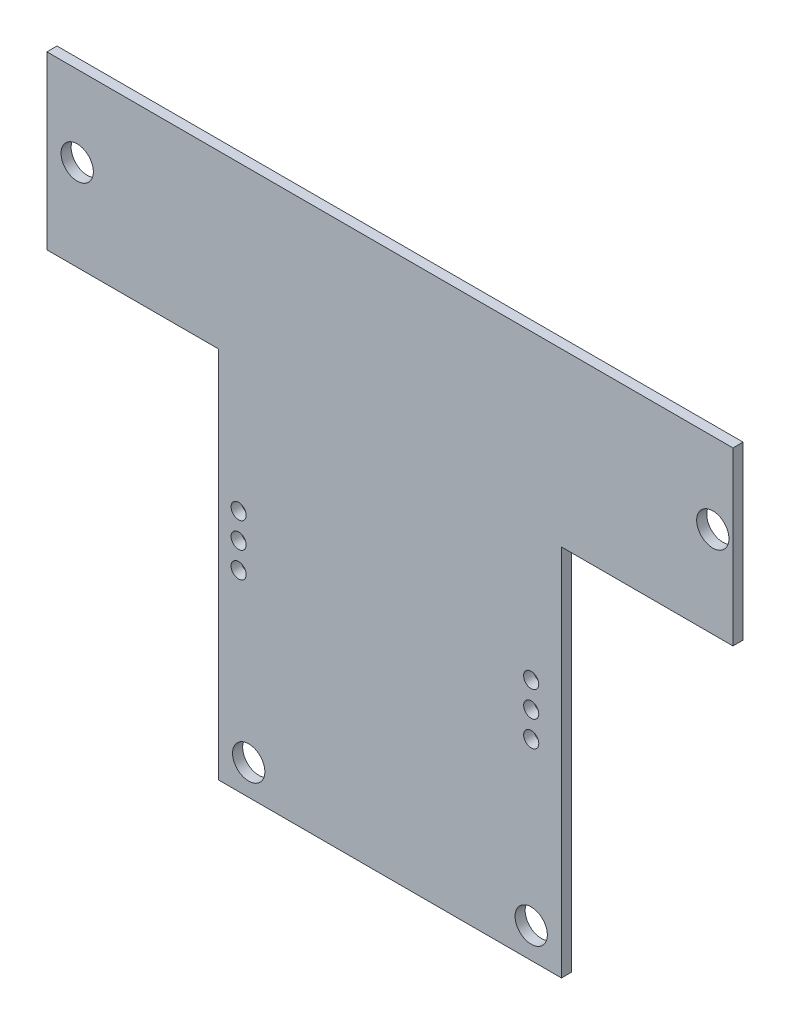
SolidWorks part; units mm, degrees
ref_plane "Ön Düzlem" through (0, 0, 0) normal (0, 0, 1) x (1, 0, 0)
ref_plane "Üst Düzlem" through (0, 0, 0) normal (0, 1, 0) x (1, 0, 0)
ref_plane "Sağ Düzlem" through (0, 0, 0) normal (1, 0, 0) x (0, 0, -1)
sketch "Çizim1" plane through (0, 0, 0) normal (0, 0, 1) x (1, 0, 0)
  line L0 (0, 0) -> (68, 0)
  line L1 (68, 0) -> (68, -17)
  line L2 (68, -17) -> (51, -17)
  line L3 (51, -17) -> (51, -54)
  line L4 (51, -54) -> (17, -54)
  line L5 (17, -54) -> (17, -17)
  line L6 (17, -17) -> (0, -17)
  line L7 (0, -17) -> (0, 0)
  line L8 (34, 0) -> (34, -54) construction
  line L9 (3, -8) -> (66, -8) construction
  line L10 (20, -51) -> (48, -51) construction
  circle A0 centre (3, -8) radius 1.6
  circle A1 centre (66, -8) radius 1.6
  circle A2 centre (20, -51) radius 1.6
  circle A3 centre (48, -51) radius 1.6
  dimension "D5" = 3.2
  dimension "D6" = 8
  dimension "D7" = 3
  dimension "D9" = 3.2
  dimension "D11" = 3.2
  dimension "D12" = 3
  dimension "D13" = 3
  dimension "D1" = 68
  dimension "D2" = 17
  dimension "D3" = 34
  dimension "D4" = 37
  dimension "D8" = 63
  dimension "D10" = 28
extrude "Yükseklik-Ekstrüzyon1" add sketch "Çizim1" along normal blind 1
sketch "Çizim2" plane through (0, 0, 1) normal (0, 0, 1) x (1, 0, 0)
  line L0 (19, -29.92) -> (19, -35) construction
  line L1 (17, -17) -> (17, -54) construction
  line L2 (48, -35) -> (48, -29.92) construction
  line L3 (17, -54) -> (51, -54) construction
  circle A0 centre (19, -35) radius 0.75
  circle A1 centre (19, -32.46) radius 0.75
  circle A2 centre (19, -29.92) radius 0.75
  circle A3 centre (48, -29.92) radius 0.75
  circle A4 centre (48, -32.46) radius 0.75
  circle A5 centre (48, -35) radius 0.75
  dimension "D1" = 1.5
  dimension "D2" = 2.54
  dimension "D3" = 2
  dimension "D4" = 19
  dimension "D5" = 31
  dimension "D6" = 19
  dimension "D7" = 2.54
extrude "Kes-Ekstrüzyon1" cut sketch "Çizim2" against normal blind 10
